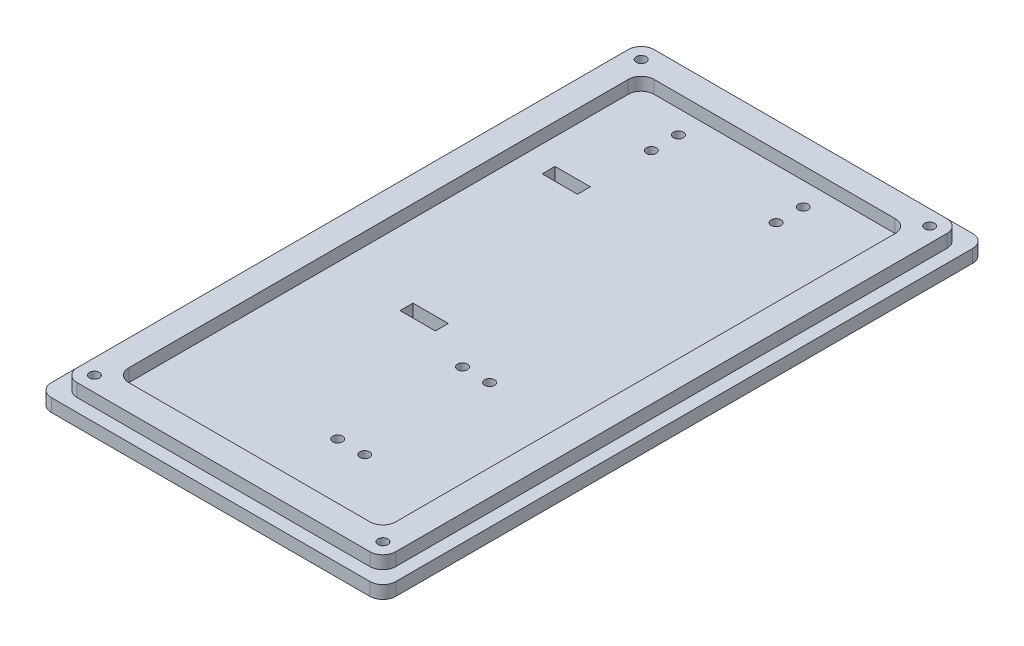
SolidWorks part; units mm, degrees
material "ABS"
ref_plane "Front Plane" through (0, 0, 0) normal (0, 0, 1) x (1, 0, 0)
ref_plane "Top Plane" through (0, 0, 0) normal (0, 1, 0) x (1, 0, 0)
ref_plane "Right Plane" through (0, 0, 0) normal (1, 0, 0) x (0, 0, -1)
sketch "Sketch1" plane through (0, 0, 0) normal (0, 1, 0) x (1, 0, 0)
  line L1 (3, 0) -> (77, 0)
  line L2 (0, 3) -> (0, 137)
  line L3 (3, 140) -> (77, 140)
  line L4 (80, 3) -> (80, 137)
  arc A0 (77, 0) -> (80, 3) centre (77, 3) ccw
  arc A1 (3, 0) -> (0, 3) centre (3, 3) cw
  arc A2 (77, 140) -> (80, 137) centre (77, 137) cw
  arc A3 (0, 137) -> (3, 140) centre (3, 137) cw
  point P9 (0, 0)
  point P12 (80, 140)
  point P15 (0, 140)
  dimension "D3" = 3
  dimension "D1" = 80
  dimension "D2" = 140
extrude "Boss-Extrude1" add sketch "Sketch1" along normal blind 3
sketch "Sketch2" plane through (0, 3, 0) normal (0, 1, 0) x (1, 0, 0)
  line L0 (0, 137) -> (0, 3) construction
  line L1 (6, 137) -> (74, 137)
  line L2 (3, 134) -> (3, 6)
  line L3 (6, 3) -> (74, 3)
  line L4 (77, 134) -> (77, 6)
  line L5 (77, 140) -> (3, 140) construction
  line L6 (80, 3) -> (80, 137) construction
  line L7 (3, 0) -> (77, 0) construction
  line L9 (12, 131) -> (68, 131)
  line L10 (9, 128) -> (9, 12)
  line L11 (12, 9) -> (68, 9)
  line L12 (71, 128) -> (71, 12)
  arc A0 (74, 137) -> (77, 134) centre (74, 134) cw
  arc A1 (74, 3) -> (77, 6) centre (74, 6) ccw
  arc A2 (3, 6) -> (6, 3) centre (6, 6) ccw
  arc A3 (6, 137) -> (3, 134) centre (6, 134) ccw
  arc A4 (9, 12) -> (12, 9) centre (12, 12) ccw
  arc A5 (68, 9) -> (71, 12) centre (68, 12) ccw
  arc A6 (68, 131) -> (71, 128) centre (68, 128) cw
  arc A7 (12, 131) -> (9, 128) centre (12, 128) ccw
  dimension "D9" = 3
  dimension "D10" = 3
  dimension "D1" = 3
  dimension "D2" = 3
  dimension "D3" = 3
  dimension "D4" = 3
  dimension "D5" = 6
  dimension "D6" = 6
  dimension "D7" = 6
  dimension "D8" = 6
extrude "Boss-Extrude2" add sketch "Sketch2" along normal blind 3
sketch "Sketch3" plane through (0, 6, 0) normal (0, 1, 0) x (1, 0, 0)
  line L0 (3, 0) -> (77, 0) construction
  line L1 (0, 137) -> (0, 3) construction
  line L2 (80, 3) -> (80, 137) construction
  line L3 (77, 140) -> (3, 140) construction
  circle A0 centre (6.5, 133.5) radius 1.15
  circle A1 centre (73.5, 133.5) radius 1.15
  circle A2 centre (73.5, 6.5) radius 1.15
  circle A3 centre (6.5, 6.5) radius 1.15
  dimension "D1" = 2.3
  dimension "D2" = 2.3
  dimension "D3" = 2.3
  dimension "D4" = 2.3
  dimension "D5" = 6.5
  dimension "D6" = 6.5
  dimension "D7" = 6.5
  dimension "D8" = 6.5
  dimension "D9" = 6.5
  dimension "D10" = 6.5
  dimension "D11" = 6.5
  dimension "D12" = 6.5
extrude "Cut-Extrude1" cut sketch "Sketch3" against normal through all
sketch "Sketch4" plane through (0, 0, 0) normal (0, -1, 0) x (1, 0, 0)
  line L0 (0, -137) -> (0, -3) construction
  line L1 (26, -58) -> (34.2, -58)
  line L2 (26, -58) -> (26, -61)
  line L3 (26, -61) -> (34.2, -61)
  line L4 (34.2, -58) -> (34.2, -61)
  line L5 (15, -102) -> (23.2, -102)
  line L6 (15, -102) -> (15, -105)
  line L7 (15, -105) -> (23.2, -105)
  line L8 (23.2, -102) -> (23.2, -105)
  line L9 (77, -140) -> (3, -140) construction
  line L10 (3, 0) -> (77, 0) construction
  dimension "D1" = 8.2
  dimension "D2" = 3
  dimension "D3" = 8.2
  dimension "D4" = 3
  dimension "D5" = 15
  dimension "D6" = 35
  dimension "D7" = 26
  dimension "D8" = 58
extrude "Cut-Extrude2" cut sketch "Sketch4" against normal blind 10
sketch "Sketch5" plane through (0, 0, 0) normal (0, -1, 0) x (1, 0, 0)
  line L0 (77, -140) -> (3, -140) construction
  line L1 (0, -137) -> (0, -3) construction
  circle A0 centre (23, -125.65) radius 1.15
  circle A1 centre (52, -125.65) radius 1.15
  circle A2 centre (52, -119.35) radius 1.15
  circle A3 centre (23, -119.35) radius 1.15
  dimension "D1" = 2.3
  dimension "D2" = 2.3
  dimension "D3" = 2.3
  dimension "D4" = 2.3
  dimension "D5" = 14.35
  dimension "D6" = 14.35
  dimension "D7" = 29
  dimension "D8" = 29
  dimension "D9" = 23
  dimension "D10" = 23
  dimension "D11" = 6.3
  dimension "D12" = 6.3
extrude "Cut-Extrude3" cut sketch "Sketch5" against normal blind 3
sketch "Sketch6" plane through (0, 0, 0) normal (0, -1, 0) x (1, 0, 0)
  line L0 (80, -3) -> (80, -137) construction
  line L1 (3, 0) -> (77, 0) construction
  circle A0 centre (50.88, -53.92) radius 1.15
  circle A1 centre (44.58, -53.92) radius 1.15
  circle A2 centre (50.88, -24.92) radius 1.15
  circle A3 centre (44.58, -24.92) radius 1.15
  dimension "D1" = 2.3
  dimension "D2" = 2.3
  dimension "D3" = 2.3
  dimension "D4" = 2.3
  dimension "D5" = 29.12
  dimension "D6" = 29.12
  dimension "D7" = 24.92
  dimension "D8" = 24.92
  dimension "D9" = 29
  dimension "D10" = 29
  dimension "D11" = 6.3
  dimension "D12" = 6.3
extrude "Cut-Extrude4" cut sketch "Sketch6" against normal blind 3
